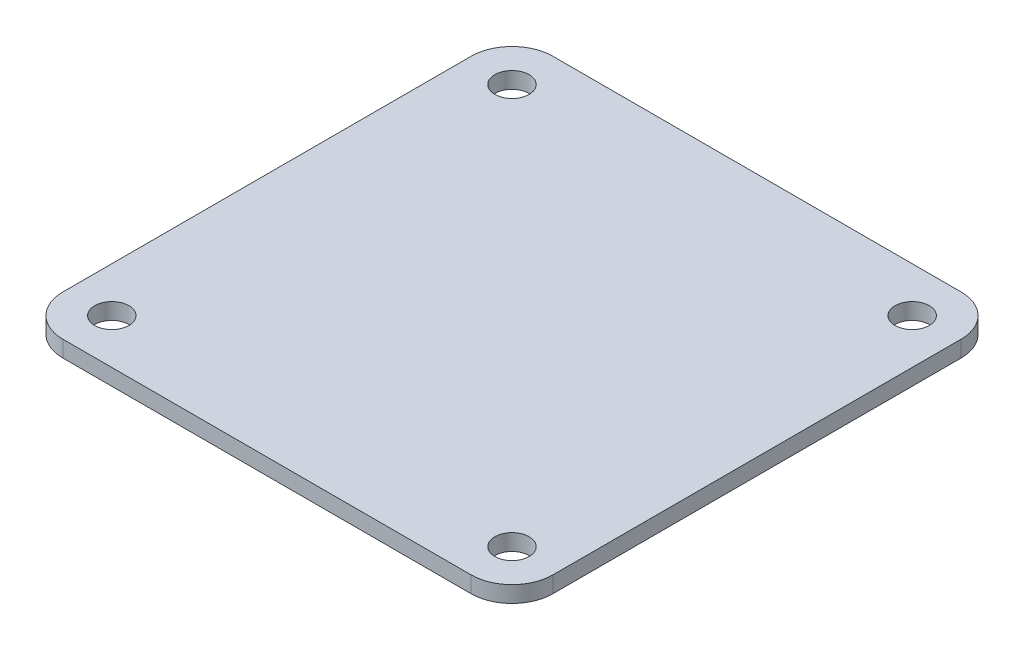
SolidWorks part; units mm, degrees
ref_plane "Front Plane" through (0, 0, 0) normal (0, 0, 1) x (1, 0, 0)
ref_plane "Top Plane" through (0, 0, 0) normal (0, 1, 0) x (1, 0, 0)
ref_plane "Right Plane" through (0, 0, 0) normal (1, 0, 0) x (0, 0, -1)
sketch "Sketch1" plane through (0, 0, 0) normal (0, 1, 0) x (1, 0, 0)
  line L1 (-12.5, -15) -> (12.5, -15)
  line L2 (-15, -12.5) -> (-15, 12.5)
  line L3 (-12.5, 15) -> (12.5, 15)
  line L4 (15, -12.5) -> (15, 12.5)
  line L5 (-15, -15) -> (15, 15) construction
  line L6 (-15, 15) -> (15, -15) construction
  line L7 (15, 15) -> (12.25, 15)
  line L8 (15, 15) -> (15, 12.25)
  line L9 (15, 12.25) -> (12.25, 12.25)
  line L10 (12.25, 15) -> (12.25, 12.25)
  line L11 (-15, 15) -> (-12.25, 15)
  line L12 (-15, 15) -> (-15, 12.25)
  line L13 (-15, 12.25) -> (-12.25, 12.25)
  line L14 (-12.25, 15) -> (-12.25, 12.25)
  line L15 (15, -15) -> (12.25, -15)
  line L16 (15, -15) -> (15, -12.25)
  line L17 (15, -12.25) -> (12.25, -12.25)
  line L18 (12.25, -15) -> (12.25, -12.25)
  line L19 (-15, -15) -> (-12.25, -15)
  line L20 (-15, -15) -> (-15, -12.25)
  line L21 (-15, -12.25) -> (-12.25, -12.25)
  line L22 (-12.25, -15) -> (-12.25, -12.25)
  circle A0 centre (12.25, 12.25) radius 1.05
  circle A1 centre (-12.25, 12.25) radius 1.05
  circle A2 centre (-12.25, -12.25) radius 1.05
  circle A3 centre (12.25, -12.25) radius 1.05
  arc A4 (-15, 12.5) -> (-12.5, 15) centre (-12.5, 12.5) cw
  arc A5 (-12.5, -15) -> (-15, -12.5) centre (-12.5, -12.5) cw
  arc A6 (12.5, -15) -> (15, -12.5) centre (12.5, -12.5) ccw
  arc A7 (12.5, 15) -> (15, 12.5) centre (12.5, 12.5) cw
  point P0 (0, 0)
  dimension "D11" = 2.1
  dimension "D12" = 2.1
  dimension "D13" = 2.1
  dimension "D14" = 2.1
  dimension "D15" = 2.5
  dimension "D1" = 30
  dimension "D2" = 30
  dimension "D3" = 2.75
  dimension "D4" = 2.75
  dimension "D5" = 2.75
  dimension "D6" = 2.75
  dimension "D7" = 2.75
  dimension "D8" = 2.75
  dimension "D9" = 2.75
  dimension "D10" = 2.75
extrude "Boss-Extrude1" add sketch "Sketch1" along normal blind 1 contours A3 L17 L4 L9 A0 L10 L3 L14 A1 L13 L2 L21 A2 L22 L1 L18 | A4 L2 L13 A1 L14 L3 | A7 L3 L10 A0 L9 L4 | L1 A6 L4 L17 A3 L18 | A5 L1 L22 A2 L21 L2
